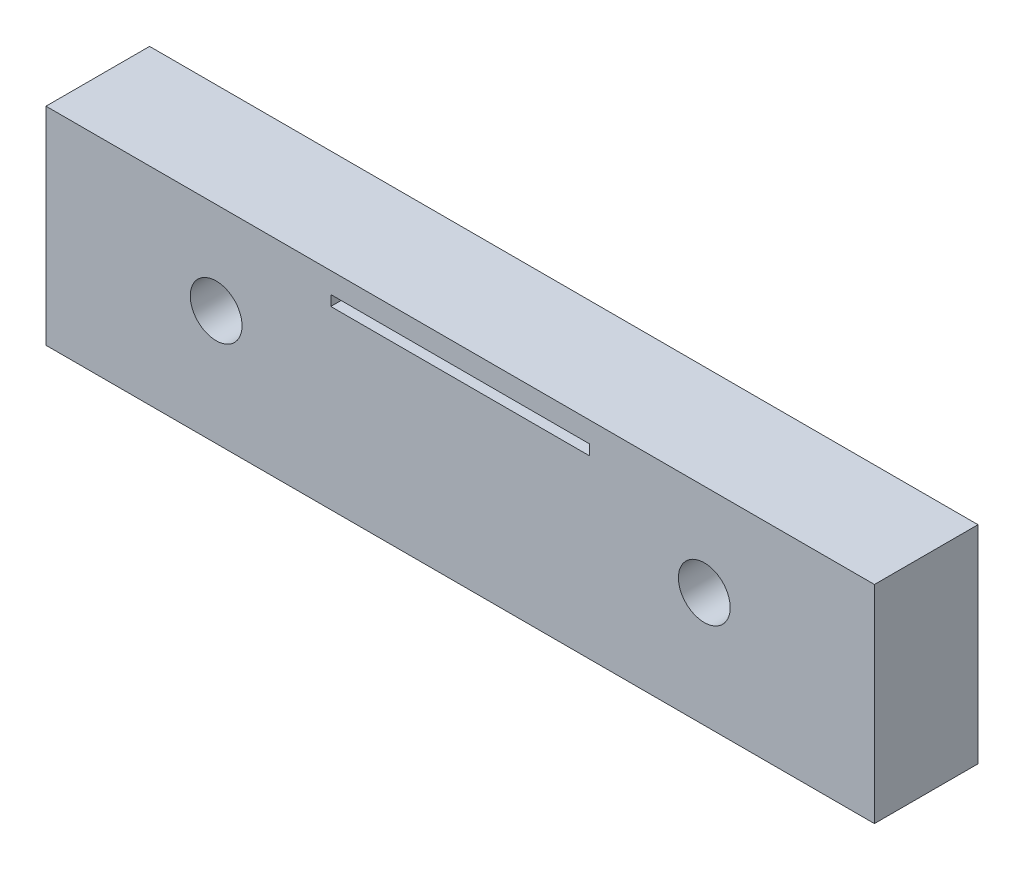
SolidWorks part; units mm, degrees
ref_plane "Front Plane" through (0, 0, 0) normal (0, 0, 1) x (1, 0, 0)
ref_plane "Top Plane" through (0, 0, 0) normal (0, 1, 0) x (1, 0, 0)
ref_plane "Right Plane" through (0, 0, 0) normal (1, 0, 0) x (0, 0, -1)
sketch "Sketch1" plane through (0, 0, 0) normal (0, 0, 1) x (1, 0, 0)
  line L1 (-40.3722, 21.485) -> (39.6278, 21.485)
  line L2 (-40.3722, 21.485) -> (-40.3722, 1.485)
  line L3 (-40.3722, 1.485) -> (39.6278, 1.485)
  line L4 (39.6278, 21.485) -> (39.6278, 1.485)
  dimension "D1" = 80
  dimension "D2" = 20
extrude "Boss-Extrude1" add sketch "Sketch1" along normal blind 10
sketch "Sketch2" plane through (0, 0, 10) normal (0, 0, 1) x (1, 0, 0)
  line L0 (39.6278, 21.485) -> (-40.3722, 21.485) construction
  line L1 (-40.3722, 21.485) -> (-40.3722, 1.485) construction
  line L2 (-0.3722, 21.485) -> (-0.3722, 1.485) construction
  line L3 (-40.3722, 1.485) -> (39.6278, 1.485) construction
  circle A0 centre (-23.9422, 12.585) radius 2.5
  circle A1 centre (23.1978, 12.585) radius 2.5
  dimension "D1" = 5
  dimension "D2" = 8.9
  dimension "D3" = 16.43
extrude "Cut-Extrude1" cut sketch "Sketch2" against normal through all
sketch "Sketch3" plane through (0, 0, 10) normal (0, 0, 1) x (1, 0, 0)
  line L0 (39.6278, 21.485) -> (-40.3722, 21.485) construction
  line L1 (-12.8722, 19.485) -> (12.1278, 19.485)
  line L2 (-12.8722, 19.485) -> (-12.8722, 18.485)
  line L3 (-12.8722, 18.485) -> (12.1278, 18.485)
  line L4 (12.1278, 19.485) -> (12.1278, 18.485)
  point P6 (-0.3722, 19.485)
  point P7 (-0.3722, 21.485)
  dimension "D1" = 1
  dimension "D2" = 2
  dimension "D3" = 25
extrude "Cut-Extrude2" cut sketch "Sketch3" against normal through all
